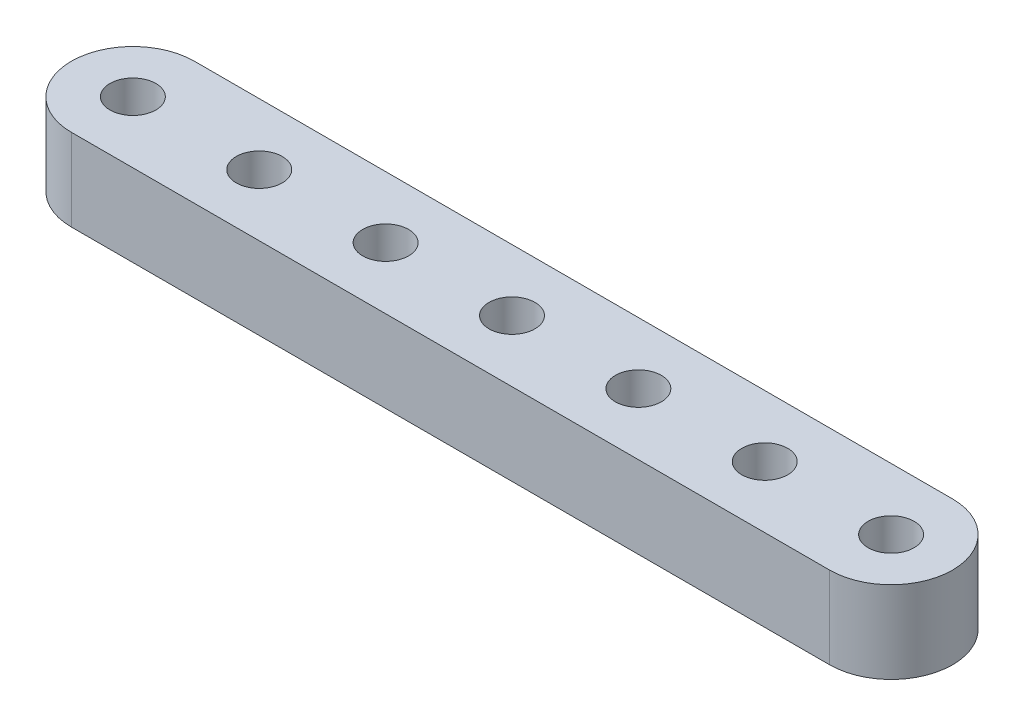
SolidWorks part; units mm, degrees
ref_plane "Front Plane" through (0, 0, 0) normal (0, 0, 1) x (1, 0, 0)
ref_plane "Top Plane" through (0, 0, 0) normal (0, 1, 0) x (1, 0, 0)
ref_plane "Right Plane" through (0, 0, 0) normal (1, 0, 0) x (0, 0, -1)
ref_plane "Plane1" through (0, 0, 0) normal (0, -1, 0) x (1, 0, 0)
sketch "Sketch1" plane through (0, 0, 0) normal (0, -1, 0) x (1, 0, 0)
  line L0 (-29.337, -4.7625) -> (29.337, -4.7625)
  line L1 (29.337, 4.7625) -> (-29.337, 4.7625)
  arc A0 (29.337, -4.7625) -> (29.337, 4.7625) centre (29.337, 0) ccw
  arc A1 (-29.337, 4.7625) -> (-29.337, -4.7625) centre (-29.337, 0) ccw
  circle A2 centre (29.337, 0) radius 1.778
  circle A3 centre (19.558, 0) radius 1.778
  circle A4 centre (9.779, 0) radius 1.778
  circle A5 centre (0, 0) radius 1.778
  circle A6 centre (-9.779, 0) radius 1.778
  circle A7 centre (-19.558, 0) radius 1.778
  circle A8 centre (-29.337, 0) radius 1.778
extrude "Boss-Extrude1" add sketch "Sketch1" against normal blind 6.35
